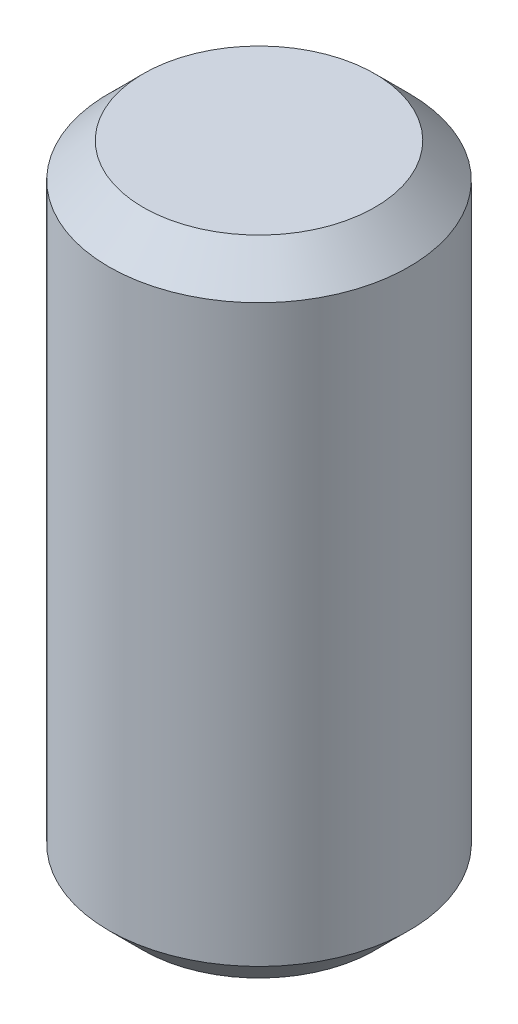
SolidWorks part; units mm, degrees
ref_plane "Front Plane" through (0, 0, 0) normal (0, 0, 1) x (1, 0, 0)
ref_plane "Top Plane" through (0, 0, 0) normal (0, 1, 0) x (1, 0, 0)
ref_plane "Right Plane" through (0, 0, 0) normal (1, 0, 0) x (0, 0, -1)
sketch "Sketch1" plane through (0, 0, 0) normal (0, 1, 0) x (1, 0, 0)
  circle A0 centre (0, 0) radius 3.5
  dimension "D1" = 7
extrude "Boss-Extrude1" add sketch "Sketch1" along normal blind 15
chamfer "Chamfer1" distance 0.8 2 edges at (0, 0, 3.5) (0, 15, 3.5)
